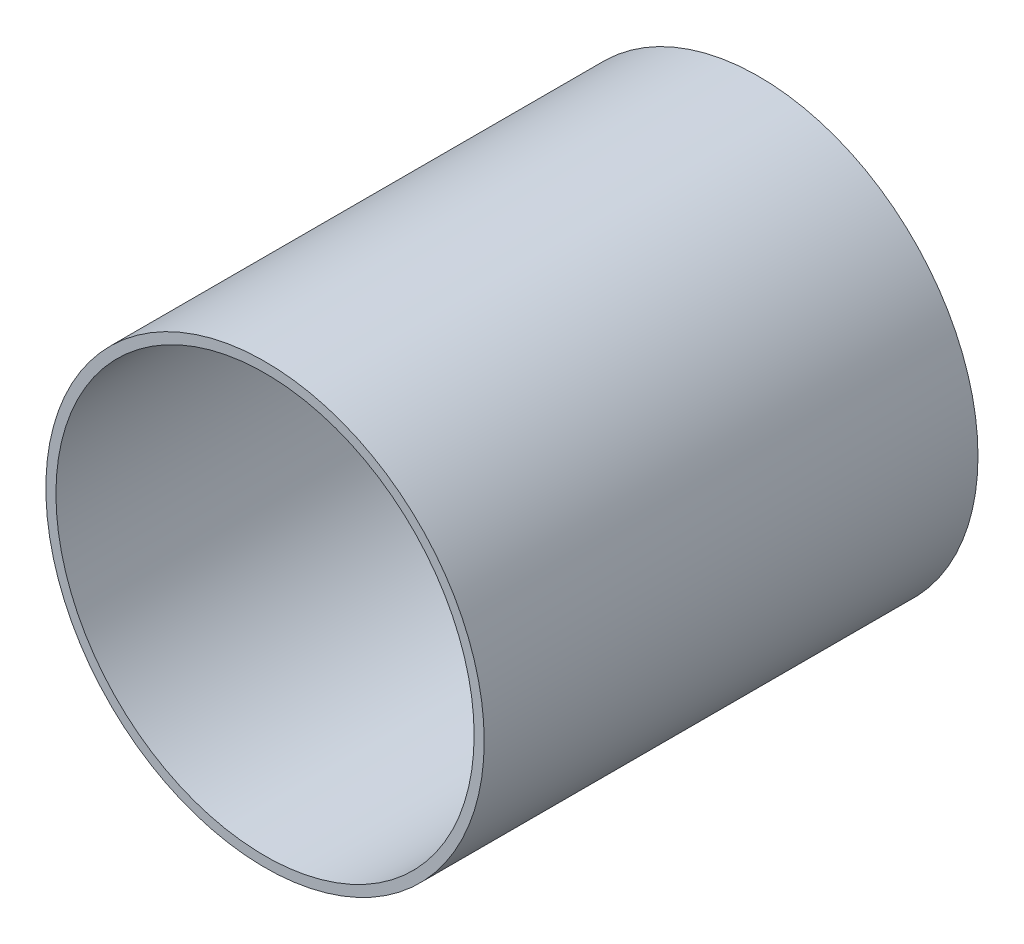
SolidWorks part; units mm, degrees
ref_plane "Plan de face" through (0, 0, 0) normal (0, 0, 1) x (1, 0, 0)
ref_plane "Plan de dessus" through (0, 0, 0) normal (0, 1, 0) x (1, 0, 0)
ref_plane "Plan de droite" through (0, 0, 0) normal (1, 0, 0) x (0, 0, -1)
sketch "Esquisse1" plane through (0, 0, 0) normal (0, 0, 1) x (1, 0, 0)
  circle A0 centre (0, 0) radius 43.5
  circle A1 centre (0, 0) radius 41.5
  dimension "D1" = 87
  dimension "D2" = 2
extrude "Boss.-Extru.1" add sketch "Esquisse1" along normal blind 98
sketch "Esquisse2" plane through (0, 0, 0) normal (0, 0, -1) x (-1, 0, 0)
  circle A0 centre (0, 0) radius 41.5
extrude "Boss.-Extru.2" add sketch "Esquisse2" against normal blind 9
